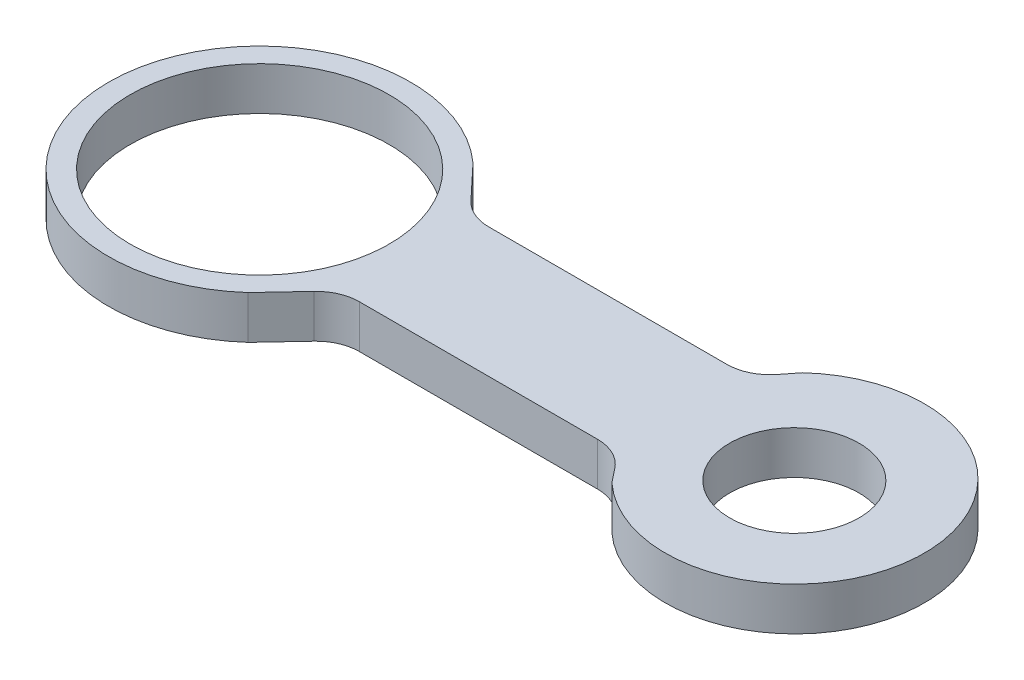
SolidWorks part; units mm, degrees
ref_plane "Front Plane" through (0, 0, 0) normal (0, 0, 1) x (1, 0, 0)
ref_plane "Top Plane" through (0, 0, 0) normal (0, 1, 0) x (1, 0, 0)
ref_plane "Right Plane" through (0, 0, 0) normal (1, 0, 0) x (0, 0, -1)
sketch "Sketch1" plane through (0, 0, 0) normal (0, 1, 0) x (1, 0, 0)
  line L0 (42.3954, 14.5042) -> (45.0142, 17.8129)
  line L1 (-20.6074, 10.7104) -> (34.5543, 10.7104)
  line L3 (-20.6074, -19.2896) -> (34.5543, -19.2896)
  line L5 (64.6933, -4.2896) -> (65.9049, -4.2896) construction
  line L7 (-27.8975, 13.8654) -> (-35.3104, 21.7604)
  line L8 (-35.3104, -30.3396) -> (-27.8975, -22.4447)
  line L10 (42.3954, -23.0834) -> (45.0142, -26.3921)
  arc A0 (-35.3104, 21.7604) -> (-35.3104, -30.3396) centre (-58.6855, -4.2896) ccw
  arc A1 (-20.6074, 10.7104) -> (-27.8975, 13.8654) centre (-20.6074, 20.7104) cw
  arc A2 (-20.6074, -19.2896) -> (-27.8975, -22.4447) centre (-20.6074, -29.2896) ccw
  circle A7 centre (65.2991, -4.2896) radius 0.6058
  arc A8 (45.0142, -26.3921) -> (45.0142, 17.8129) centre (65.2991, -4.2896) ccw
  arc A9 (42.3954, -23.0834) -> (34.5543, -19.2896) centre (34.5543, -29.2896) ccw
  arc A10 (42.3954, 14.5042) -> (34.5543, 10.7104) centre (34.5543, 20.7104) cw
  point P0 (0, 0)
  point P21 (39.3926, -19.2896)
  point P26 (39.3926, 10.7104)
  dimension "D1" = 10
  dimension "D2" = 10
  dimension "D3" = 30
  dimension "D4" = 10
  dimension "D5" = 30
  dimension "D6" = 35
  dimension "D7" = 60
  dimension "D8" = 60
extrude "Boss-Extrude1" add sketch "Sketch1" along normal blind 10
sketch "Sketch3" plane through (0, 10, 0) normal (0, 1, 0) x (1, 0, 0)
  circle A0 centre (-58.6855, -4.2896) radius 30
  circle A1 centre (65.6642, -4.773) radius 15
  circle A2 centre (65.2991, -4.2896) radius 0.6058 construction
  dimension "D1" = 60
  dimension "D2" = 30
extrude "Cut-Extrude1" cut sketch "Sketch3" against normal blind 10
